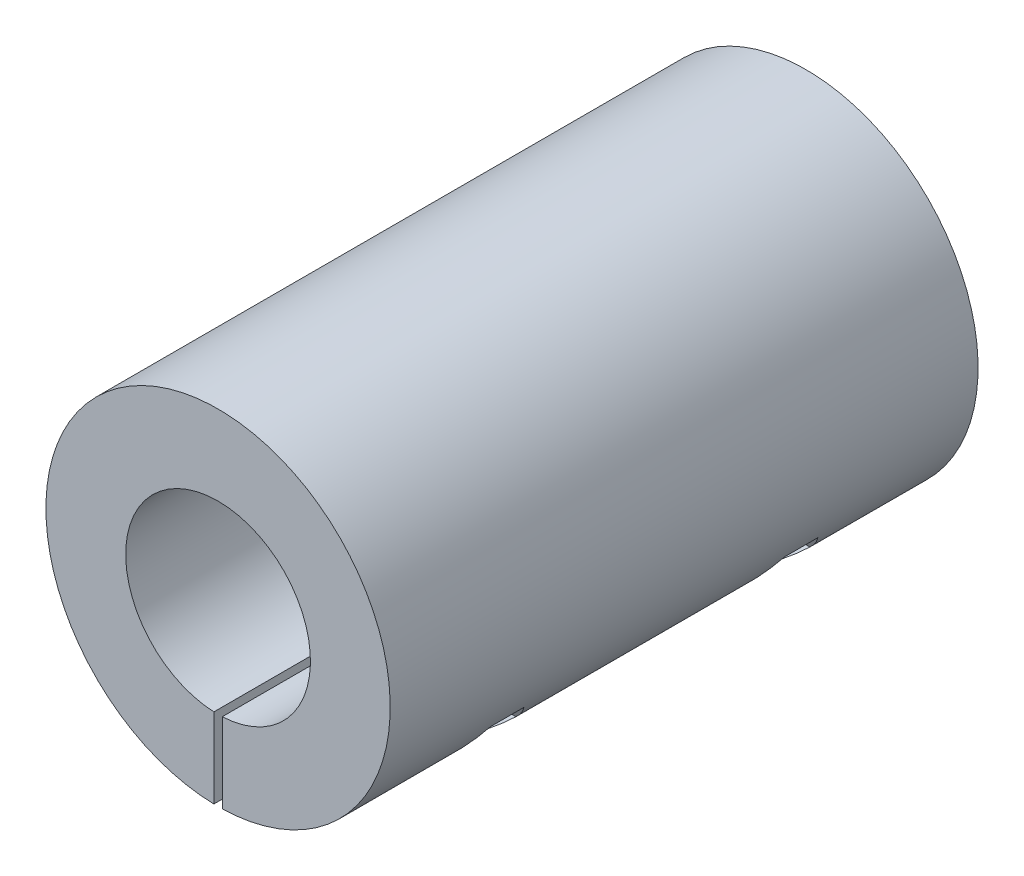
SolidWorks part; units mm, degrees
ref_plane "Front Plane" through (0, 0, 0) normal (0, 0, 1) x (1, 0, 0)
ref_plane "Top Plane" through (0, 0, 0) normal (0, 1, 0) x (1, 0, 0)
ref_plane "Right Plane" through (0, 0, 0) normal (1, 0, 0) x (0, 0, -1)
sketch "Sketch1" plane through (0, 0, 0) normal (0, 0, 1) x (1, 0, 0)
  circle A0 centre (0, 0) radius 11.5
  circle A1 centre (0, 0) radius 20.5
  dimension "D1" = 23
  dimension "D2" = 41
extrude "Boss-Extrude1" add sketch "Sketch1" along normal blind 35
sketch "Sketch2" plane through (0, 0, 35) normal (0, 0, 1) x (1, 0, 0)
  circle A0 centre (0, 0) radius 11
  circle A1 centre (0, 0) radius 20.5
  dimension "D1" = 22
extrude "Boss-Extrude2" add sketch "Sketch2" along normal blind 35
sketch "Sketch3" plane through (0, 0, 0) normal (0, 0, -1) x (-1, 0, 0)
  line L1 (-0.5, 0) -> (0.5, 0)
  line L2 (-0.5, 0) -> (-0.5, -20.5)
  line L3 (-0.5, -20.5) -> (0.5, -20.5)
  line L4 (0.5, 0) -> (0.5, -20.5)
  line L5 (-0.5, 0) -> (0.5, -20.5) construction
  line L6 (-0.5, -20.5) -> (0.5, 0) construction
  circle A0 centre (0, 0) radius 20.5 construction
  point P0 (0, -10.25)
  point P5 (0, 0)
  point P7 (0, -4.4559)
  point P8 (0, 0)
  dimension "D1" = 1
extrude "Cut-Extrude1" cut sketch "Sketch3" against normal up to surface (70 mm away) up to face at (20.5, 0, 70)
sketch "Sketch4" plane through (0, 0, 0) normal (1, 0, 0) x (0, 0, -1)
  line L0 (-35, -10.9886) -> (-35, -11.4891) construction
  line L1 (-70, -15.7413) -> (-35, -15.7413) construction
  line L2 (0, -11.4891) -> (-35, -11.4891) construction
  line L3 (-70, -20.4939) -> (-70, -10.9886) construction
  line L5 (-35, -15.7413) -> (0, -15.7413) construction
  line L6 (0, -20.4939) -> (0, -11.4891) construction
  circle A0 centre (-52.5, -14.9891) radius 2
  circle A1 centre (-17.5, -14.9891) radius 2
  point P5 (0, 0)
  point P12 (-52.5, -15.7413)
  point P13 (0, 0)
  point P14 (-17.601, -16.3535)
  point P15 (-54.0101, -13.6272)
  point P16 (-17.4837, -12.777)
  point P19 (-52.5, -13.9538)
  point P20 (-17.5, -15.7413)
  point P21 (-52.5, -13.5991)
  dimension "D1" = 4
  dimension "D2" = 3.5
extrude "Cut-Extrude2" cut sketch "Sketch4" against normal up to surface and the other way up to surface up to face at (0, 0.003, 35) other way up to face at (0, 0.003, 35)
ref_plane "Plane1" through (4, 0, 0) normal (1, 0, 0) x (0, 0, -1)
ref_plane "Plane2" through (-4, 0, 0) normal (1, 0, 0) x (0, 0, -1)
sketch "Sketch6" plane through (4, 0, 0) normal (1, 0, 0) x (0, 0, -1)
  line L1 (-48.5163, -14.9891) -> (-50.5081, -11.5391)
  line L2 (-50.5081, -11.5391) -> (-54.4919, -11.5391)
  line L3 (-54.4919, -11.5391) -> (-56.4837, -14.9891)
  line L4 (-56.4837, -14.9891) -> (-54.4919, -18.4391)
  line L5 (-54.4919, -18.4391) -> (-50.5081, -18.4391)
  line L6 (-50.5081, -18.4391) -> (-48.5163, -14.9891)
  line L7 (-13.5163, -14.9891) -> (-15.5081, -11.5391)
  line L8 (-15.5081, -11.5391) -> (-19.4919, -11.5391)
  line L9 (-19.4919, -11.5391) -> (-21.4837, -14.9891)
  line L10 (-21.4837, -14.9891) -> (-19.4919, -18.4391)
  line L11 (-19.4919, -18.4391) -> (-15.5081, -18.4391)
  line L12 (-15.5081, -18.4391) -> (-13.5163, -14.9891)
  circle A0 centre (-52.5, -14.9891) radius 3.45 construction
  circle A1 centre (-17.5, -14.9891) radius 3.45 construction
  point P10 (-55.07, -11.0453)
  dimension "D1" = 6.9
extrude "Cut-Extrude3" cut sketch "Sketch6" along normal up to surface (4.9582 mm away)
sketch "Sketch7" plane through (-4, 0, 0) normal (1, 0, 0) x (0, 0, -1)
  circle A0 centre (-52.5, -14.9891) radius 3.6
  circle A1 centre (-17.5, -14.9891) radius 3.6
  dimension "D1" = 7.2
extrude "Cut-Extrude4" cut sketch "Sketch7" against normal up to surface (9.9849 mm away)
